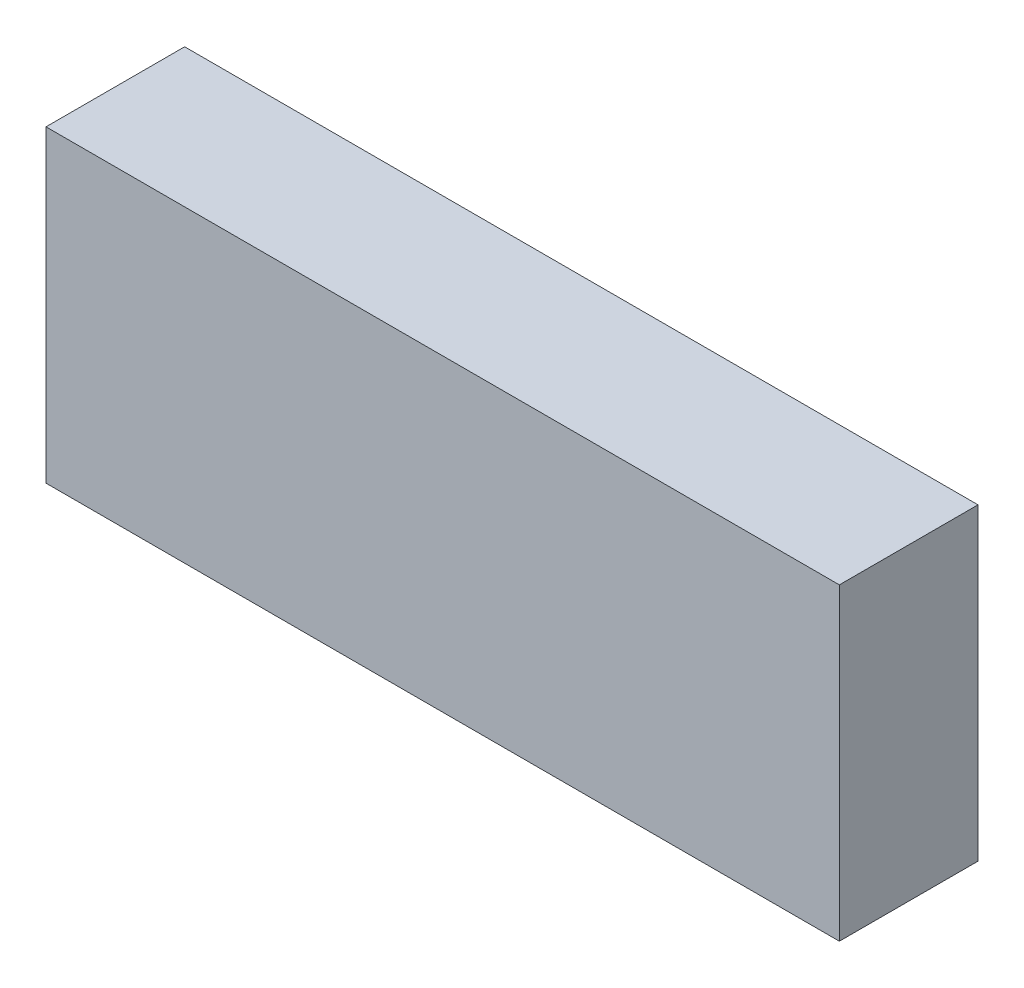
SolidWorks part; units mm, degrees
ref_plane "Front Plane" through (0, 0, 0) normal (0, 0, 1) x (1, 0, 0)
ref_plane "Top Plane" through (0, 0, 0) normal (0, 1, 0) x (1, 0, 0)
ref_plane "Right Plane" through (0, 0, 0) normal (1, 0, 0) x (0, 0, -1)
sketch "Sketch1" plane through (0, 0, 0) normal (0, 0, 1) x (1, 0, 0)
  line L1 (0, 0) -> (72.6741, 0)
  line L2 (0, 0) -> (0, 28.2712)
  line L3 (0, 28.2712) -> (72.6741, 28.2712)
  line L4 (72.6741, 0) -> (72.6741, 28.2712)
extrude "Boss-Extrude1" add sketch "Sketch1" along normal blind 12.7
